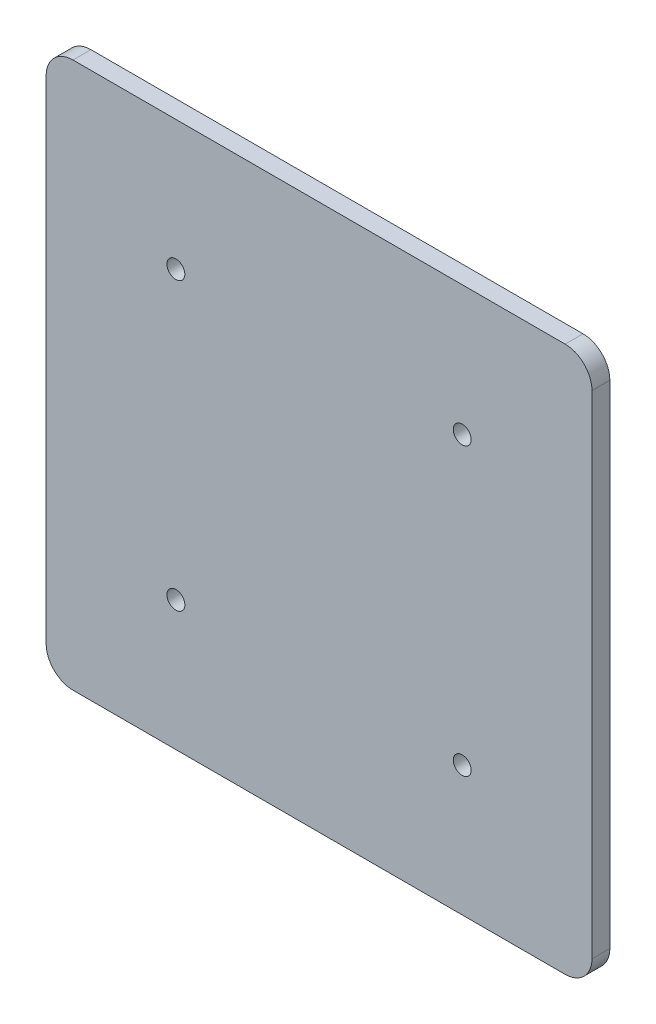
SolidWorks part; units mm, degrees
ref_plane "Plan de face" through (0, 0, 0) normal (0, 0, 1) x (1, 0, 0)
ref_plane "Plan de dessus" through (0, 0, 0) normal (0, 1, 0) x (1, 0, 0)
ref_plane "Plan de droite" through (0, 0, 0) normal (1, 0, 0) x (0, 0, -1)
sketch "Esquisse1" plane through (0, 0, 0) normal (0, 0, 1) x (1, 0, 0)
  line L1 (-152.5, -152.5) -> (152.5, -152.5)
  line L2 (-152.5, -152.5) -> (-152.5, 152.5)
  line L3 (-152.5, 152.5) -> (152.5, 152.5)
  line L4 (152.5, -152.5) -> (152.5, 152.5)
  dimension "D1" = 152.5
  dimension "D2" = 305
  dimension "D3" = 305
  dimension "D4" = 152.5
extrude "Boss.-Extru.1" add sketch "Esquisse1" along normal blind 10
fillet "Congé2" radius 15 4 edges at (152.5, 152.5, 5) (152.5, -152.5, 5) (-152.5, -152.5, 5) (-152.5, 152.5, 5)
sketch "Esquisse3" plane through (0, 0, 10) normal (0, 0, 1) x (1, 0, 0)
  line L1 (-100, -100) -> (100, -100) construction
  line L2 (-100, -100) -> (-100, 100) construction
  line L3 (-100, 100) -> (100, 100) construction
  line L4 (100, -100) -> (100, 100) construction
  line L5 (-80, -80) -> (80, -80) construction
  line L6 (-80, -80) -> (-80, 80) construction
  line L7 (-80, 80) -> (80, 80) construction
  line L8 (80, -80) -> (80, 80) construction
  circle A0 centre (80, 80) radius 5
  circle A1 centre (80, -80) radius 5
  circle A2 centre (-80, -80) radius 5
  circle A3 centre (-80, 80) radius 5
  point P4 (0, 0)
  dimension "D9" = 10
  dimension "D10" = 10
  dimension "D11" = 10
  dimension "D12" = 10
  dimension "D1" = 200
  dimension "D2" = 200
  dimension "D3" = 100
  dimension "D4" = 100
  dimension "D5" = 20
  dimension "D6" = 20
  dimension "D7" = 20
  dimension "D8" = 20
extrude "Enlèv. mat.-Extru.11" cut sketch "Esquisse3" against normal blind 10
